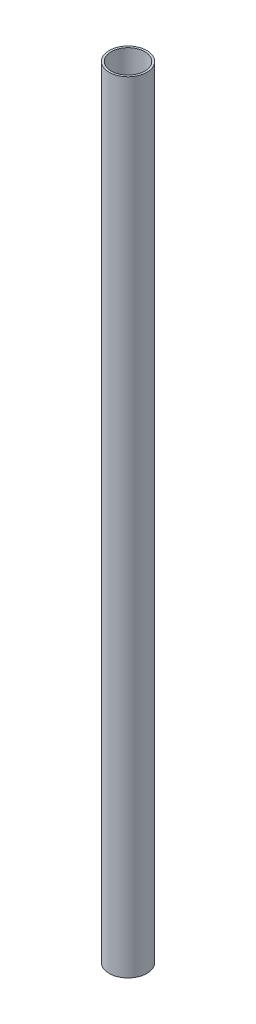
SolidWorks part; units mm, degrees
ref_plane "Front Plane" through (0, 0, 0) normal (0, 0, 1) x (1, 0, 0)
ref_plane "Top Plane" through (0, 0, 0) normal (0, 1, 0) x (1, 0, 0)
ref_plane "Right Plane" through (0, 0, 0) normal (1, 0, 0) x (0, 0, -1)
sketch "Sketch1" plane through (0, 0, 0) normal (0, 1, 0) x (1, 0, 0)
  circle A0 centre (0, 0) radius 11.665
  circle A1 centre (0, 0) radius 10.395
  dimension "D1" = 23.33
  dimension "D2" = 1.27
extrude "Boss-Extrude1" add sketch "Sketch1" along normal mid plane 482.6
